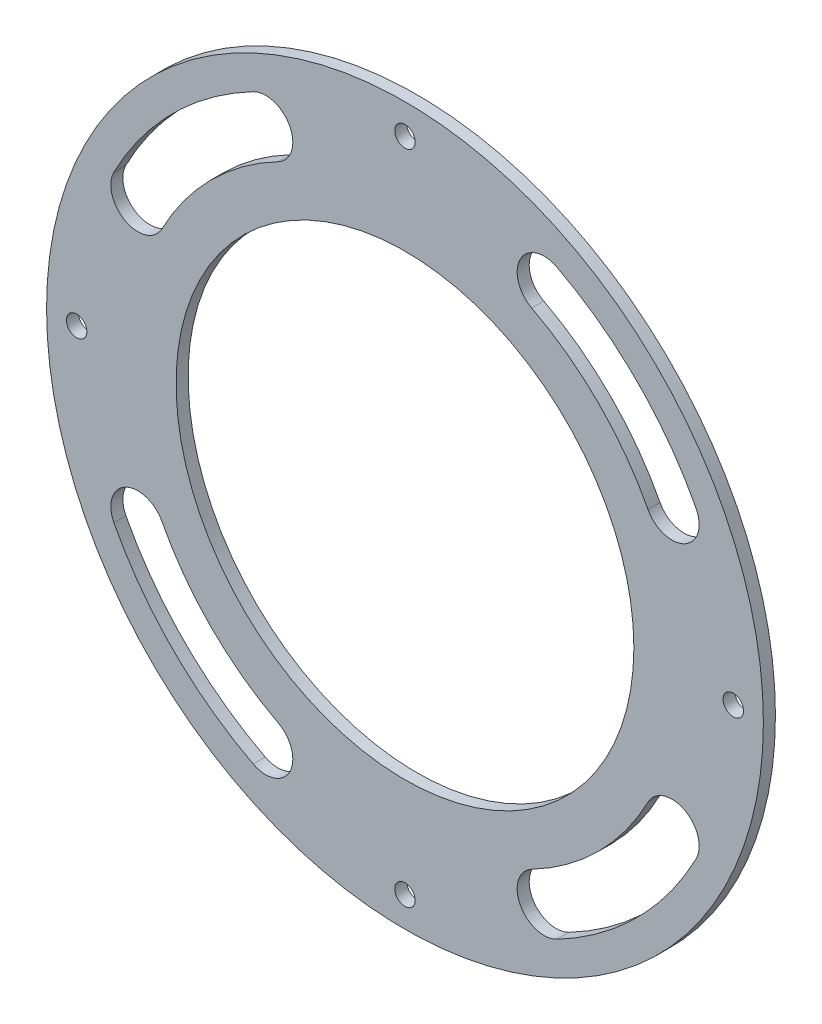
SolidWorks part; units mm, degrees
ref_plane "前视基准面" through (0, 0, 0) normal (0, 0, 1) x (1, 0, 0)
ref_plane "上视基准面" through (0, 0, 0) normal (0, 1, 0) x (1, 0, 0)
ref_plane "右视基准面" through (0, 0, 0) normal (1, 0, 0) x (0, 0, -1)
other "Configuration Table"
sketch "草图1" plane through (0, 0, 0) normal (0, 0, 1) x (1, 0, 0)
  line L0 (0, -54.5) -> (0, 54.5) construction
  line L1 (-18, 24) -> (18, 24)
  line L2 (-18, 24) -> (-18, -24)
  line L3 (-18, -24) -> (18, -24)
  line L4 (18, 24) -> (18, -24)
  line L5 (-18, 24) -> (18, -24) construction
  line L6 (-18, -24) -> (18, 24) construction
  line L7 (-54.5, 59.5) -> (54.5, 59.5) construction
  line L8 (-54.5, 59.5) -> (-54.5, -59.5) construction
  line L9 (-54.5, -59.5) -> (54.5, -59.5) construction
  line L10 (54.5, 59.5) -> (54.5, -59.5) construction
  line L11 (-54.5, 59.5) -> (54.5, -59.5) construction
  line L12 (-54.5, -59.5) -> (54.5, 59.5) construction
  circle A0 centre (0, 0) radius 54.5 construction
  circle A5 centre (-18, 24) radius 1.7
  circle A6 centre (18, 24) radius 1.7
  circle A7 centre (18, -24) radius 1.7
  circle A8 centre (-18, -24) radius 1.7
  circle A9 centre (0, 54.5) radius 1.7
  circle A10 centre (54.5, 0) radius 1.7
  circle A11 centre (0, -54.5) radius 1.7
  circle A12 centre (-54.5, 0) radius 1.7
  circle A13 centre (0, 0) radius 59.5
  point P0 (0, 0)
  point P6 (0, 0)
  point P33 (0, 0)
  dimension "D5" = 109
  dimension "D6" = 5
  dimension "D7" = 3.4
  dimension "D8" = 3.4
  dimension "D1" = 36
  dimension "D2" = 48
  dimension "D3" = 109
  dimension "D4" = 119
  dimension "D9" = 4
extrude "凸台-拉伸4" add sketch "草图1" along normal blind 2
sketch "草图2" plane through (0, 0, 2) normal (0, 0, 1) x (1, 0, 0)
  circle A0 centre (0, 0) radius 38
  dimension "D1" = 76
extrude "切除-拉伸1" cut sketch "草图2" against normal blind 2
sketch "草图4" plane through (0, 0, 2) normal (0, 0, 1) x (1, 0, 0)
  line L0 (0, 0) -> (42.0729, 42.0729) construction
  line L1 (0, 54.5) -> (0, 0) construction
  circle A0 centre (0, 0) radius 45.5
  circle A1 centre (0, 0) radius 54.5
  arc A2 (40.3434, 21.0394) -> (48.3235, 25.2011) centre (44.3334, 23.1202) ccw
  arc A3 (25.2011, 48.3235) -> (21.0394, 40.3434) centre (23.1202, 44.3334) ccw
  circle A4 centre (0, 0) radius 59.5 construction
  dimension "D1" = 109
  dimension "D2" = 9
  dimension "D3" = 30
  dimension "D4" = 50
  dimension "D5" = 9
  dimension "D6" = 45
extrude "切除-拉伸3" cut sketch "草图4" against normal blind 2 contours A1 A3 A0 A2
pattern_circular "阵列(圆周)2" count 4 every 90 about axis through (0, 0, 0) along (0, 0, 1) of "切除-拉伸3"
